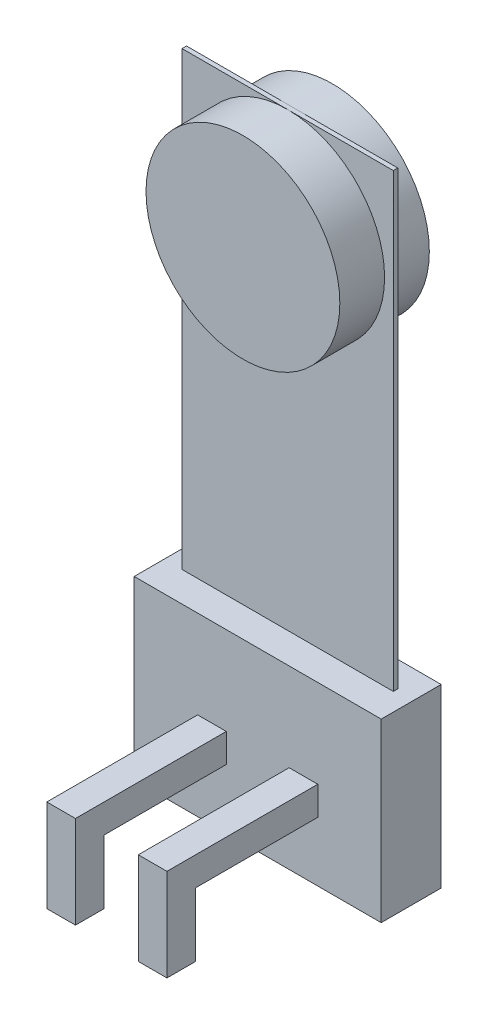
SolidWorks part; units mm, degrees
ref_plane "Front Plane" through (0, 0, 0) normal (0, 0, 1) x (1, 0, 0)
ref_plane "Top Plane" through (0, 0, 0) normal (0, 1, 0) x (1, 0, 0)
ref_plane "Right Plane" through (0, 0, 0) normal (1, 0, 0) x (0, 0, -1)
sketch "Sketch1" plane through (0, 0, 0) normal (0, 0, 1) x (1, 0, 0)
  line L1 (0, 0) -> (5.9944, 0)
  line L2 (0, 0) -> (0, 12.8016)
  line L3 (0, 12.8016) -> (5.9944, 12.8016)
  line L4 (5.9944, 0) -> (5.9944, 12.8016)
  dimension "D1" = 12.8016
  dimension "D2" = 5.9944
extrude "Boss-Extrude1" add sketch "Sketch1" along normal blind 0.127
sketch "Sketch2" plane through (0, 0, 0.127) normal (0, 0, 1) x (1, 0, 0)
  line L0 (0, 0) -> (5.9944, 0) construction
  line L1 (-0.508, 0) -> (6.5024, 0)
  line L2 (-0.508, 0) -> (-0.508, -5.0038)
  line L3 (-0.508, -5.0038) -> (6.5024, -5.0038)
  line L4 (6.5024, 0) -> (6.5024, -5.0038)
  line L5 (5.9944, 0) -> (5.9944, 12.8016) construction
  line L6 (0, 12.8016) -> (0, 0) construction
  dimension "D1" = 0.508
  dimension "D2" = 0.508
  dimension "D3" = 5.0038
extrude "Boss-Extrude2" add sketch "Sketch2" along normal blind 0.8509 and the other way blind 0.8509
sketch "Sketch3" plane through (0, 0, 0.127) normal (0, 0, 1) x (1, 0, 0)
  line L0 (5.9944, 12.8016) -> (0, 12.8016) construction
  circle A0 centre (2.9972, 10.0516) radius 2.75
  dimension "D1" = 5.5
extrude "Boss-Extrude3" add sketch "Sketch3" along normal blind 1.27 and the other way blind 1.27
sketch "Sketch4" plane through (-0.508, 0, 0) normal (-1, 0, 0) x (0, 0, 1)
  line L0 (0.9779, -3.3147) -> (4.445, -3.3147)
  line L1 (0.9779, 0) -> (0.9779, -5.0038) construction
  line L2 (4.445, -3.3147) -> (4.445, -5.1238)
  line L3 (4.445, -5.1238) -> (5.2578, -5.1238)
  line L4 (5.2578, -5.1238) -> (5.2578, -2.5019)
  line L5 (5.2578, -2.5019) -> (0.9779, -2.5019)
  line L6 (-1.143, 12.8016) -> (-1.143, 7.3016) construction
  line L7 (0.9779, -3.3147) -> (0.9779, -2.5019)
  dimension "D1" = 0.8128
  dimension "D2" = 0.8128
  dimension "D3" = 6.4008
extrude "Boss-Extrude4" add sketch "Sketch4" against normal blind 7.0104 contours L5 L7 L0 L2 L3 L4
sketch "Sketch5" plane through (0, -2.5019, 0) normal (0, 1, 0) x (1, 0, 0)
  line L0 (6.5024, -5.2578) -> (-0.508, -5.2578) construction
  line L1 (-0.508, -0.9779) -> (1.2927, -0.9779)
  line L2 (-0.508, -0.9779) -> (-0.508, -5.2578)
  line L3 (-0.508, -5.2578) -> (1.2927, -5.2578)
  line L4 (1.2927, -0.9779) -> (1.2927, -5.2578)
  line L6 (2.1055, -5.2578) -> (3.8889, -5.2578)
  line L7 (2.1055, -5.2578) -> (2.1055, -0.9779)
  line L8 (2.1055, -0.9779) -> (3.8889, -0.9779)
  line L9 (3.8889, -5.2578) -> (3.8889, -0.9779)
  line L10 (6.5024, -5.2578) -> (4.7017, -5.2578)
  line L11 (6.5024, -5.2578) -> (6.5024, -0.9779)
  line L12 (6.5024, -0.9779) -> (4.7017, -0.9779)
  line L13 (4.7017, -5.2578) -> (4.7017, -0.9779)
  dimension "D1" = 0.8128
  dimension "D2" = 0.8128
extrude "Cut-Extrude1" cut sketch "Sketch5" against normal blind 7.0104
